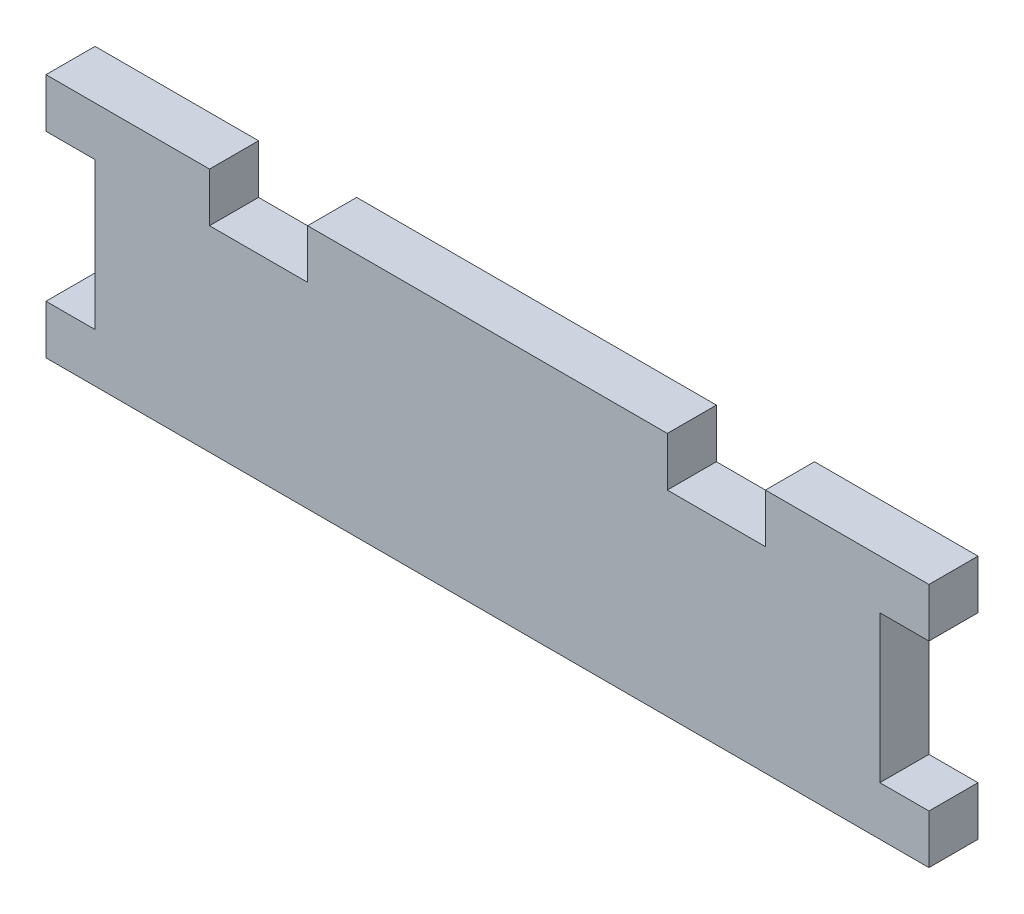
SolidWorks part; units mm, degrees
ref_plane "Front Plane" through (0, 0, 0) normal (0, 0, 1) x (1, 0, 0)
ref_plane "Top Plane" through (0, 0, 0) normal (0, 1, 0) x (1, 0, 0)
ref_plane "Right Plane" through (0, 0, 0) normal (1, 0, 0) x (0, 0, -1)
sketch "Sketch1" plane through (0, 0, 0) normal (0, 0, 1) x (1, 0, 0)
  line L1 (0, 0) -> (54, 0)
  line L2 (0, 0) -> (0, 15)
  line L3 (0, 15) -> (54, 15)
  line L4 (54, 0) -> (54, 15)
  line L5 (0, 12) -> (3, 12)
  line L6 (0, 12) -> (0, 3)
  line L7 (0, 3) -> (3, 3)
  line L8 (3, 12) -> (3, 3)
  line L9 (54, 12) -> (51, 12)
  line L10 (54, 12) -> (54, 3)
  line L11 (54, 3) -> (51, 3)
  line L12 (51, 12) -> (51, 3)
  line L13 (10, 15) -> (16, 15)
  line L14 (10, 15) -> (10, 12)
  line L15 (10, 12) -> (16, 12)
  line L16 (16, 15) -> (16, 12)
  line L17 (44, 15) -> (38, 15)
  line L18 (44, 15) -> (44, 12)
  line L19 (44, 12) -> (38, 12)
  line L20 (38, 15) -> (38, 12)
  dimension "D1" = 15
  dimension "D2" = 54
  dimension "D3" = 3
  dimension "D4" = 3
  dimension "D5" = 3
  dimension "D6" = 10
  dimension "D7" = 6
  dimension "D8" = 10
  dimension "D9" = 6
extrude "Boss-Extrude1" add sketch "Sketch1" along normal blind 3 contours L20 L3 L16 L15 L14 L2 L5 L8 L7 L1 L4 L11 L12 L9 L18 L19
